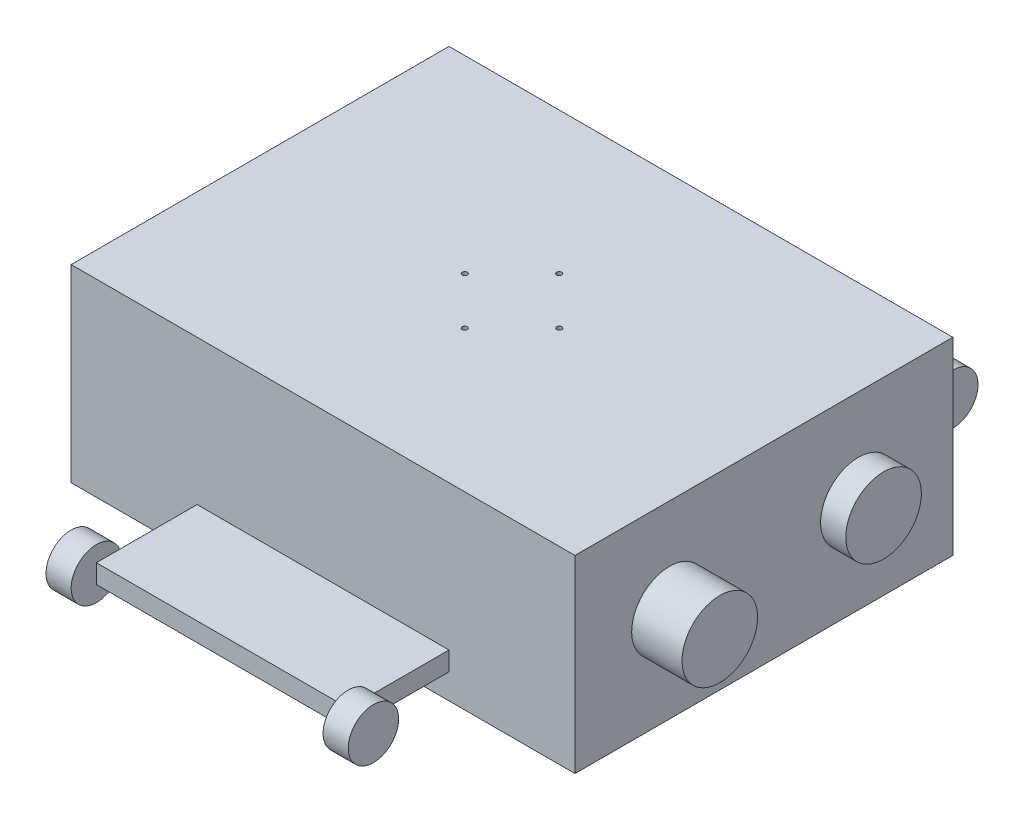
SolidWorks part; units mm, degrees
ref_plane "前视基准面" through (0, 0, 0) normal (0, 0, 1) x (1, 0, 0)
ref_plane "上视基准面" through (0, 0, 0) normal (0, 1, 0) x (1, 0, 0)
ref_plane "右视基准面" through (0, 0, 0) normal (1, 0, 0) x (0, 0, -1)
sketch "草图1" plane through (0, 0, 0) normal (0, 0, 1) x (1, 0, 0)
  line L1 (-200, 75) -> (200, 75)
  line L2 (-200, 75) -> (-200, -75)
  line L3 (-200, -75) -> (200, -75)
  line L4 (200, 75) -> (200, -75)
  line L5 (-200, 75) -> (200, -75) construction
  line L6 (-200, -75) -> (200, 75) construction
  point P0 (0, 0)
  dimension "D1" = 400
  dimension "D2" = 150
extrude "凸台-拉伸1" add sketch "草图1" against normal blind 300
sketch "草图2" plane through (200, 0, 0) normal (1, 0, 0) x (0, 0, -1)
  line L0 (0, 0) -> (300, 0) construction
  line L1 (300, -75) -> (300, 75) construction
  line L2 (150, -75) -> (150, 75) construction
  line L3 (300, 75) -> (0, 75) construction
  circle A0 centre (75, 0) radius 30
  circle A1 centre (225, 0) radius 30
  point P10 (150, 0)
  dimension "D1" = 60
  dimension "D2" = 60
  dimension "D3" = 75
  dimension "D4" = 75
extrude "凸台-拉伸2" add sketch "草图2" along normal blind 20
sketch "草图3" plane through (220, 0, 0) normal (1, 0, 0) x (0, 0, -1)
  circle A1 centre (75, 0) radius 30
  dimension "D1" = 60
extrude "凸台-拉伸3" add sketch "草图3" along normal blind 20
sketch "草图5" plane through (0, 0, 0) normal (1, 0, 0) x (0, 0, -1)
  line L0 (150, 75) -> (150, -75) construction
  line L1 (300, 75) -> (0, 75) construction
  line L2 (300, -75) -> (0, -75) construction
sketch "草图6" plane through (-200, 0, 0) normal (-1, 0, 0) x (0, 0, 1)
  line L0 (-300, 0) -> (0, 0) construction
  line L1 (-300, 75) -> (-300, -75) construction
  line L2 (-150, -75) -> (-150, 75) construction
  circle A0 centre (-225, 0) radius 30
  circle A1 centre (-75, 0) radius 30
  point P9 (-150, 0)
  dimension "D1" = 60
  dimension "D2" = 60
  dimension "D3" = 75
  dimension "D4" = 75
extrude "凸台-拉伸4" add sketch "草图6" along normal blind 20
sketch "草图7" plane through (-220, 0, 0) normal (-1, 0, 0) x (0, 0, 1)
  circle A0 centre (-225, 0) radius 30
  dimension "D1" = 60
extrude "凸台-拉伸5" add sketch "草图7" along normal blind 20
sketch "草图8" plane through (0, 0, 0) normal (0, 0, 1) x (1, 0, 0)
  line L0 (0, 75) -> (0, -75) construction
  line L1 (100, -55) -> (-100, -55)
  line L2 (100, -55) -> (100, -40)
  line L3 (100, -40) -> (-100, -40)
  line L4 (-100, -55) -> (-100, -40)
  line L5 (100, -55) -> (-100, -40) construction
  line L6 (100, -40) -> (-100, -55) construction
  point P0 (0, -47.5)
  dimension "D1" = 200
  dimension "D2" = 15
  dimension "D3" = 40
extrude "凸台-拉伸6" add sketch "草图8" along normal blind 80
ref_plane "基准面1" through (0, 0, -150) normal (0, 0, 1) x (1, 0, 0)
mirror "镜向2" about plane through (0, 0, -150) normal (0, 0, 1) of "凸台-拉伸6"
sketch "草图9" plane through (100, 0, 0) normal (1, 0, 0) x (0, 0, -1)
  line L0 (-80, -55) -> (-80, -40) construction
  circle A0 centre (-80, -47.5) radius 20
  dimension "D1" = 40
extrude "凸台-拉伸7" add sketch "草图9" along normal blind 20
mirror "镜向3" about plane through (0, 0, -150) normal (0, 0, 1) of "凸台-拉伸7"
mirror "镜向4" about plane through (0, 0, 0) normal (1, 0, 0) of "镜向3", "凸台-拉伸7"
sketch "草图10" plane through (0, 75, 0) normal (0, 1, 0) x (1, 0, 0)
  line L0 (-200, 300) -> (200, 0) construction
  circle A0 centre (0, 150) radius 37.5 construction
  circle A1 centre (0, 187.5) radius 2
  circle A2 centre (37.5, 150) radius 2
  circle A3 centre (0, 112.5) radius 2
  circle A4 centre (-37.5, 150) radius 2
  dimension "D1" = 75
  dimension "D2" = 4
extrude "切除-拉伸1" cut sketch "草图10" against normal blind 10
